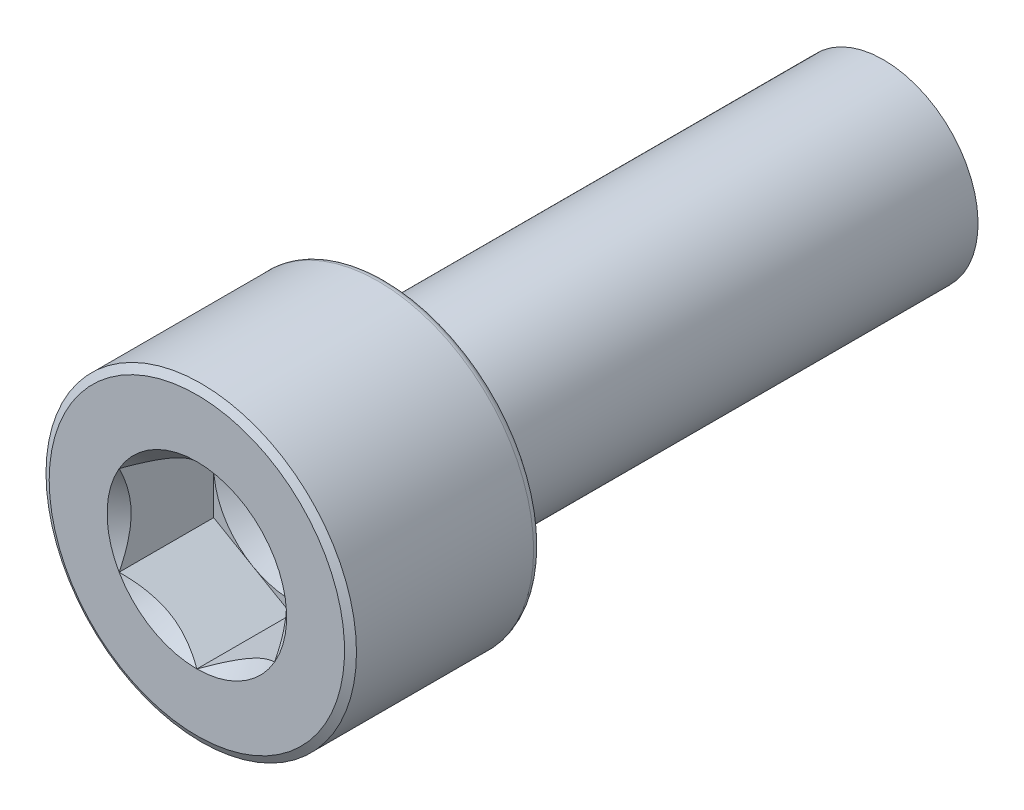
SolidWorks part; units mm, degrees
material "AISI 1020"
ref_plane "Front" through (0, 0, 0) normal (0, 0, 1) x (1, 0, 0)
ref_plane "Top" through (0, 0, 0) normal (0, 1, 0) x (1, 0, 0)
ref_plane "Right" through (0, 0, 0) normal (1, 0, 0) x (0, 0, -1)
sketch "Sketch1" plane through (0, 0, 0) normal (1, 0, 0) x (0, 0, -1)
  line L0 (0, 0) -> (-0.635, 0) construction
  line L1 (0, 0) -> (12.7, 0)
  line L2 (0, 0) -> (0, 2.413)
  line L3 (0, 2.413) -> (12.7, 2.413)
  line L4 (12.7, 0) -> (12.7, 2.413)
  line L5 (0, -2.413) -> (12.7, -2.413) construction
  dimension "D1" = 0.635
  dimension "Thread Dia" = 4.826
  dimension "Screw Length" = 12.7
revolve "Revolve1" add sketch "Sketch1" angle 360 about L0
sketch "Sketch4" plane through (0, 0, 0) normal (0, 0, 1) x (1, 0, 0)
  circle A0 centre (0, 0) radius 3.9624
  dimension "Head Dia" = 7.9248
extrude "Extrude1" add sketch "Sketch4" along normal blind 4.826
fillet "Fillet1" radius 0.193 1 edges at (3.9624, 0, 0)
chamfer "Chamfer1" distance 0.193 angle 30 1 edges at (3.9624, 0, 4.826)
sketch "Sketch6" plane through (0, 0, 4.826) normal (0, 0, 1) x (1, 0, 0)
  line L1 (0, -2.2914) -> (1.9844, -1.1457)
  line L2 (1.9844, -1.1457) -> (1.9844, 1.1457)
  line L3 (1.9844, 1.1457) -> (0, 2.2914)
  line L4 (0, 2.2914) -> (-1.9844, 1.1457)
  line L5 (-1.9844, 1.1457) -> (-1.9844, -1.1457)
  line L6 (-1.9844, -1.1457) -> (0, -2.2914)
  circle A0 centre (0, 0) radius 1.9844 construction
  dimension "Hex" = 3.9688
extrude "Cut-Extrude1" cut sketch "Sketch6" against normal blind 2.413
sketch "Sketch7" plane through (0, 0, 4.826) normal (0, 0, 1) x (1, 0, 0)
  circle A0 centre (0, 0) radius 2.2914
extrude "Cut-Extrude4" cut sketch "Sketch7" against normal blind 2.413 draft 45
sketch "Sketch8" plane through (0, 0, 2.413) normal (0, 0, 1) x (1, 0, 0)
  circle A0 centre (0, 0) radius 1.9844 construction
  circle A1 centre (0, 0) radius 1.9844
extrude "Cut-Extrude5" cut sketch "Sketch8" against normal blind 0.8043 draft 60
